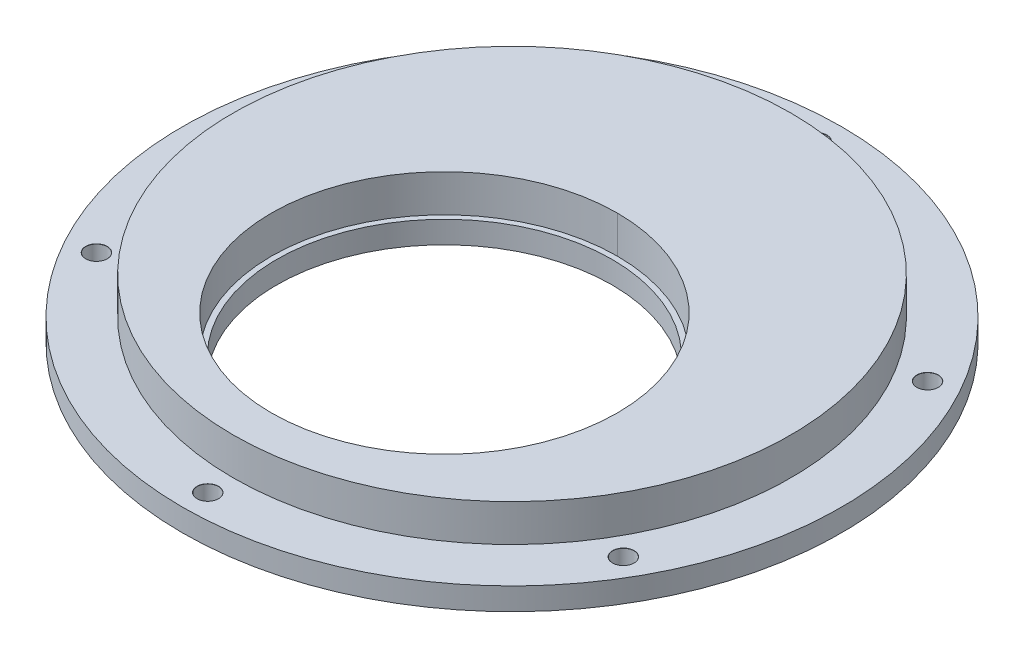
SolidWorks part; units mm, degrees
material "6061-T6 (SS)"
ref_plane "X-Y Datum" through (0, 0, 0) normal (0, 0, 1) x (1, 0, 0)
ref_plane "X-Z Datum" through (0, 0, 0) normal (0, 1, 0) x (1, 0, 0)
ref_plane "Y-Z Datum" through (0, 0, 0) normal (1, 0, 0) x (0, 0, -1)
sketch "Sketch1" plane through (0, 0, 0) normal (0, 1, 0) x (1, 0, 0)
  line L0 (0, 0) -> (0, -12.7) construction
  line L1 (0, -43.0151) -> (0, 43.0151) construction
  line L2 (0, 52.3875) -> (0, 61.9125) construction
  circle A0 centre (0, -12.7) radius 30.988
  circle A1 centre (0, 0) radius 52.3875 construction
  circle A2 centre (0, 0) radius 61.9125
  circle A3 centre (0, 0) radius 57.15 construction
  point P12 (0, 57.15)
  dimension "D2" = 61.976
  dimension "D3" = 104.775
  dimension "D4" = 123.825
  dimension "D5" = 114.3
  dimension "D1" = 12.7
extrude "Slotted-Body Extrude" add sketch "Sketch1" along normal blind 4.191
sketch "Sketch5" plane through (0, 4.191, 0) normal (0, 1, 0) x (1, 0, 0)
  circle A0 centre (0, 0) radius 52.3875 construction
  circle A1 centre (0, 0) radius 52.3875
extrude "Boss-Extrude3" add sketch "Sketch5" along normal blind 6.985
sketch "Sketch6" plane through (0, 0, 0) normal (0, -1, 0) x (1, 0, 0)
  line L0 (0, -79.2756) -> (0, 0) construction
  circle A0 centre (0, 12.7) radius 30.988 construction
  circle A1 centre (0, 12.7) radius 30.988 construction
  circle A2 centre (0, 12.7) radius 32.512
  circle A21 centre (0, 0) radius 61.9125 construction
  point P30 (0, 0)
  point P31 (-3.014, -23.2419)
  point P32 (0, 0)
  point P36 (-3.014, -46.8932)
  dimension "D1" = 65.024
extrude "Cut-Extrude5" cut sketch "Sketch6" against normal through all
sketch "Sketch8" plane through (0, 0, 0) normal (0, -1, 0) x (1, 0, 0)
  circle A0 centre (0, 12.7) radius 32.512 construction
  circle A1 centre (0, 12.7) radius 32.512
  circle A2 centre (0, 12.7) radius 31.496
  dimension "D1" = 62.992
extrude "Boss-Extrude4" add sketch "Sketch8" against normal blind 4.16 separate body
hole_wizard "Ø4.0mm Dowel Hole2" positions "Sketch9" profile "Sketch10" hole size "Ø4.0" standard "ANSI Metric" end condition through all
sketch "Sketch9" plane through (0, 4.191, 0) normal (0, 1, 0) x (1, 0, 0)
  point P0 (0, 57.15)
sketch "Sketch10" plane through (0, 4.191, -57.15) normal (1, 0, 0) x (0, 0, 1)
  line L0 (0, 0) -> (0, 4.191)
  line L1 (0, 4.191) -> (2, 4.191)
  line L2 (2, 4.191) -> (2, 0.025)
  line L3 (2, 0.025) -> (2.025, 0)
  line L5 (2.025, 0) -> (0, 0)
  line L6 (-2, 0.025) -> (-2.025, 0) construction
  line L11 (0, -6.35) -> (0, 107.95) construction
  dimension "Thru Hole Dia." = 4
  dimension "Thru Hole Depth" = 4.191
  dimension "Near C'Sink Dia." = 4.05
  dimension "Near C'Sink Angle" = 90
pattern_circular "CirPattern1" count 6 every 60 about axis through (0, 0, 0) along (0, 1, 0) of "Ø4.0mm Dowel Hole2"
ref_point "Point1"
ref_plane "Plane1" through (0, 0, 0) normal (1, 0, 0) x (0, 0, -1)
split line "Split Line1"
ref_point "Point4"
ref_point "Point5"
split line "Split Line2"
split line "Split Line3"
